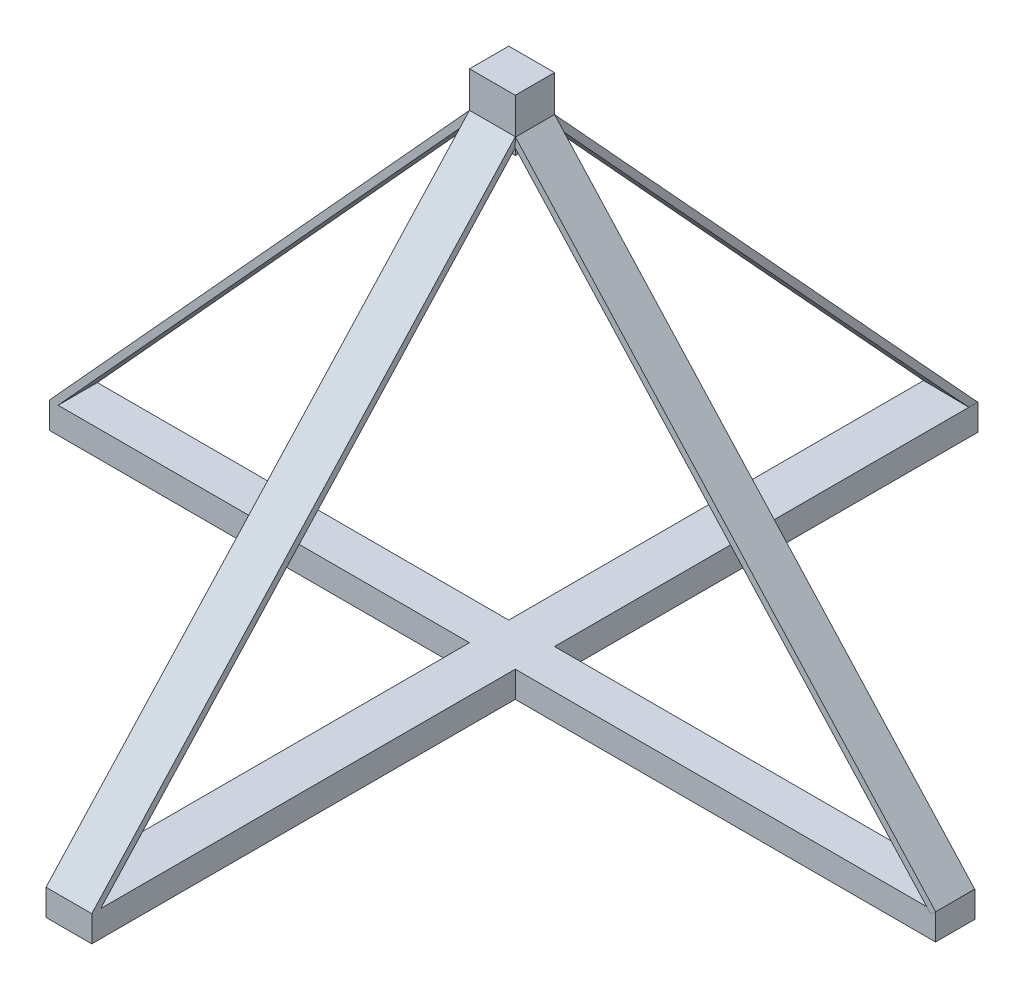
SolidWorks part; units mm, degrees
ref_plane "Front Plane" through (0, 0, 0) normal (0, 0, 1) x (1, 0, 0)
ref_plane "Top Plane" through (0, 0, 0) normal (0, 1, 0) x (1, 0, 0)
ref_plane "Right Plane" through (0, 0, 0) normal (1, 0, 0) x (0, 0, -1)
sketch "Sketch1" plane through (0, 0, 0) normal (0, 1, 0) x (1, 0, 0)
  line L1 (0, 0) -> (88.9, 0)
  line L2 (0, 0) -> (0, -1720.85)
  line L3 (0, -1720.85) -> (88.9, -1720.85)
  line L4 (88.9, 0) -> (88.9, -1720.85)
  line L5 (0, -822.325) -> (-815.975, -822.325)
  line L6 (0, -822.325) -> (0, -898.525)
  line L7 (0, -898.525) -> (-815.975, -898.525)
  line L8 (-815.975, -822.325) -> (-815.975, -898.525)
  line L9 (88.9, -822.325) -> (905.002, -822.325)
  line L10 (88.9, -822.325) -> (88.9, -898.525)
  line L11 (88.9, -898.525) -> (905.002, -898.525)
  line L12 (905.002, -822.325) -> (905.002, -898.525)
  point P5 (0, -860.425)
  point P6 (88.9, -860.425)
  point P15 (0, 0)
  point P16 (0, 0)
  point P17 (0, 0)
  point P18 (-815.975, -860.425)
  point P19 (0, 0)
  point P20 (905.002, -860.425)
  dimension "D1" = 1720.85
  dimension "D2" = 88.9
  dimension "D3" = 815.975
  dimension "D4" = 76.2
  dimension "D5" = 76.2
  dimension "D6" = 816.102
extrude "Boss-Extrude1" add sketch "Sketch1" along normal blind 50.8 contours L4 L1 L2 L3 | L5 L8 L7 L2 | L9 L12 L11 L10
ref_plane "Plane1" through (0, 914.4, 0) normal (0, 1, 0) x (1, 0, 0)
sketch "Sketch2" plane through (0, 914.4, 0) normal (0, 1, 0) x (1, 0, 0)
  line L1 (0, -898.525) -> (88.9, -898.525)
  line L2 (0, -898.525) -> (0, -822.325)
  line L3 (0, -822.325) -> (88.9, -822.325)
  line L4 (88.9, -898.525) -> (88.9, -822.325)
  point P6 (0, 0)
  point P9 (0, 0)
extrude "Boss-Extrude2" add sketch "Sketch2" along normal blind 101.6 separate body
sketch3d "3DSketch1"
  line L0 (0, 946.1455, 898.525) -> (88.9, 946.1455, 898.525)
  line L1 (0, 1016, 898.525) -> (0, 914.4, 898.525) construction
  line L2 (88.9, 1016, 898.525) -> (88.9, 914.4, 898.525) construction
  line L3 (0, 946.1455, 898.525) -> (0, 946.1455, 821.8921)
  line L4 (0, 946.1455, 821.8921) -> (88.9, 945.4056, 822.325)
  line L5 (88.9, 1016, 822.325) -> (88.9, 914.4, 822.325) construction
  line L8 (88.9, 946.1455, 898.525) -> (88.9, 945.4056, 822.325)
ref_plane "Plane5" through (0.3205, 23.5232, -25.6082) normal (0.0092, 0.6765, -0.7364) x (-1, 0.0062, -0.0068)
ref_plane "Plane6" through (0, 880.565, 958.7571) normal (0, -0.6764, -0.7365) x (-1, 0, 0)
ref_plane "Plane7" through (-471.0419, 429.285, 0) normal (-0.7391, 0.6736, 0) x (0, 0, 1)
ref_plane "Plane8" through (515.2398, 469.8321, -4.5622) normal (-0.7389, -0.6738, 0.0065) x (0.0048, 0.0044, 1)
sketch "Sketch11" plane through (515.2398, 469.8321, -4.5622) normal (-0.7389, -0.6738, 0.0065) x (0.0048, 0.0044, 1)
  line L7 (826.9049, 638.6756) -> (903.1049, 638.6756)
  line L8 (826.9049, 638.6756) -> (826.9049, -572.2503)
  line L9 (826.9049, -572.2503) -> (903.1049, -572.2503)
  line L10 (903.1049, 638.6756) -> (903.1049, -572.2503)
extrude "Boss-Extrude6" add sketch "Sketch11" along normal blind 12.7
sketch "Sketch12" plane through (0, 880.565, 958.7571) normal (0, -0.6764, -0.7365) x (-1, 0, 0)
  line L1 (-88.9, -1126.6302) -> (0, -1126.6302)
  line L2 (-88.9, -1126.6302) -> (-88.9, 89.0433)
  line L3 (-88.9, 89.0433) -> (0, 89.0433)
  line L4 (0, -1126.6302) -> (0, 89.0433)
extrude "Boss-Extrude7" add sketch "Sketch12" along normal blind 12.7
sketch "Sketch13" plane through (-471.0419, 429.285, 0) normal (-0.7391, 0.6736, 0) x (0, 0, 1)
  line L0 (822.325, -512.0837) -> (898.525, -512.0837) construction
  line L1 (822.325, -512.0837) -> (898.525, -512.0837)
  line L2 (822.325, -512.0837) -> (822.325, 699.3034)
  line L3 (822.325, 699.3034) -> (898.525, 699.3034)
  line L4 (898.525, -512.0837) -> (898.525, 699.3034)
  line L5 (898.525, 37.5467) -> (898.525, -512.0837) construction
  line L6 (898.525, 699.3034) -> (821.8921, 699.3034) construction
  point P6 (0, 0)
extrude "Boss-Extrude8" add sketch "Sketch13" against normal blind 12.7
sketch "Sketch14" plane through (0.3205, 23.5232, -25.6082) normal (0.0092, 0.6765, -0.7364) x (-1, 0.0062, -0.0068)
  line L0 (0.3167, 37.4117) -> (-88.5795, 37.4117) construction
  line L1 (-88.5795, 37.4117) -> (0.3167, 37.4117)
  line L2 (-88.5795, 37.4117) -> (-88.5795, 1252.5403)
  line L3 (-88.5795, 1252.5403) -> (0.3167, 1252.7923)
  line L4 (0.3167, 37.4117) -> (0.3167, 1252.7923)
  line L6 (0.3205, 1252.7923) -> (-88.5833, 1252.5403) construction
  point P6 (0, 0)
  point P8 (0, 0)
extrude "Boss-Extrude9" add sketch "Sketch14" against normal blind 12.7
